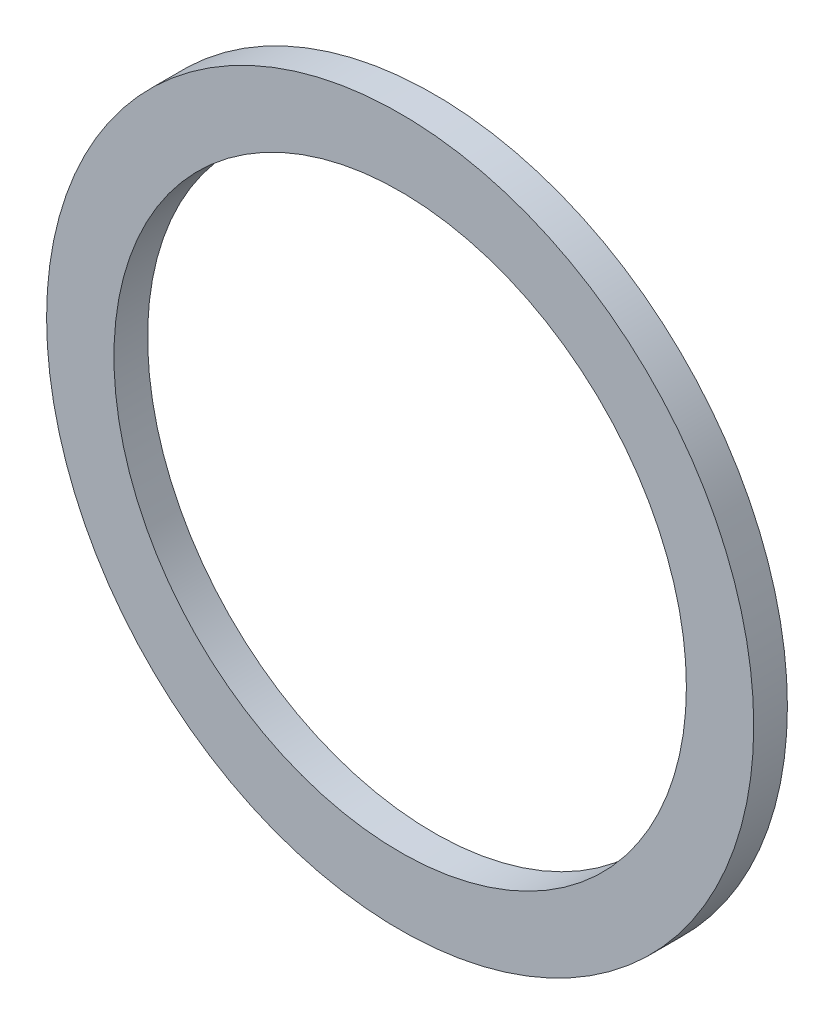
SolidWorks part; units mm, degrees
material "Copper"
ref_plane "Front Plane" through (0, 0, 0) normal (0, 0, 1) x (1, 0, 0)
ref_plane "Top Plane" through (0, 0, 0) normal (0, 1, 0) x (1, 0, 0)
ref_plane "Right Plane" through (0, 0, 0) normal (1, 0, 0) x (0, 0, -1)
sketch "Sketch1" plane through (0, 0, 0) normal (0, 0, 1) x (1, 0, 0)
  circle A0 centre (0, 0) radius 21
  circle A1 centre (0, 0) radius 17
  dimension "D1" = 42
  dimension "D2" = 34
extrude "Boss-Extrude1" add sketch "Sketch1" along normal blind 2
